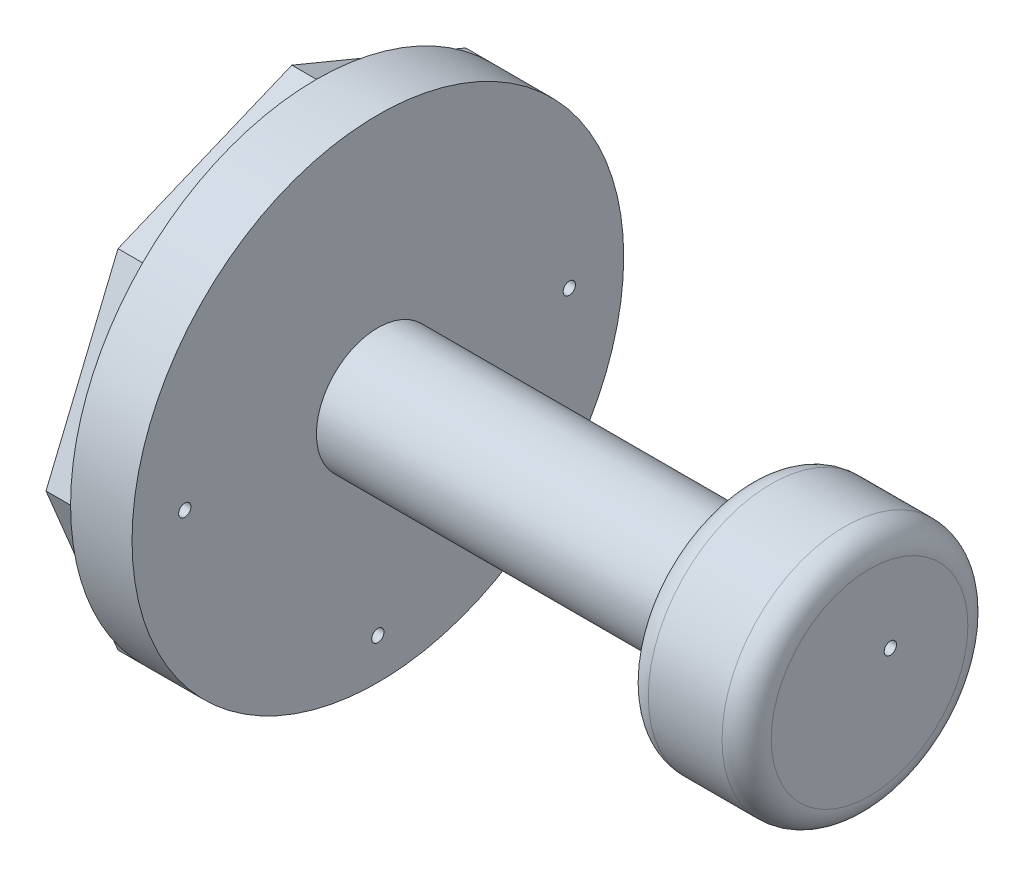
SolidWorks part; units mm, degrees
ref_plane "Front Plane" through (0, 0, 0) normal (0, 0, 1) x (1, 0, 0)
ref_plane "Top Plane" through (0, 0, 0) normal (0, 1, 0) x (1, 0, 0)
ref_plane "Right Plane" through (0, 0, 0) normal (1, 0, 0) x (0, 0, -1)
sketch "Sketch1" plane through (0, 0, 0) normal (0, 0, 1) x (1, 0, 0)
  line L17 (-22.5, 0) -> (22.5, 0)
  line L18 (22.5, 0) -> (22.5, 5)
  line L20 (22.5, 5) -> (22.5, 10)
  line L21 (22.5, 10) -> (12.5, 10)
  line L22 (12.5, 10) -> (12.5, 5)
  line L23 (12.5, 5) -> (-17.5, 5)
  line L24 (-17.5, 5) -> (-17.5, 20)
  line L25 (-17.5, 20) -> (-22.5, 20)
  line L26 (-22.5, 20) -> (-22.5, 0)
  point P0 (0, 0)
  dimension "D5" = 30
  dimension "D6" = 5
  dimension "D7" = 5
  dimension "D1" = 10
  dimension "D2" = 20
  dimension "D3" = 5
  dimension "D4" = 5
revolve "Revolve2" add sketch "Sketch1" angle 360 about L17
fillet "Fillet7" radius 2 1 edges at (22.5, 0, 10)
fillet "Fillet8" radius 2 1 edges at (12.5, 0, 10)
sketch "Sketch2" plane through (-22.5, 0, 0) normal (-1, 0, 0) x (0, 0, 1)
  line L0 (0, 20) -> (-14.1421, 14.1421)
  line L1 (-14.1421, 14.1421) -> (-20, 0)
  line L2 (-20, 0) -> (-14.1421, -14.1421)
  line L3 (-14.1421, -14.1421) -> (0, -20)
  line L4 (0, -20) -> (14.1421, -14.1421)
  line L5 (14.1421, -14.1421) -> (20, 0)
  line L6 (20, 0) -> (14.1421, 14.1421)
  line L7 (14.1421, 14.1421) -> (0, 20)
  line L8 (0, 20) -> (0, -20) construction
  line L9 (-5.3835, 14.7091) -> (-1.3333, 10.3779)
  line L10 (-1.3333, 10.3779) -> (-3.8507, 9.4935)
  line L11 (-11.5701, -4.6843) -> (11.7573, -4.6843)
  line L12 (-7.5, -6.4936) -> (7.5, -6.4936)
  line L13 (-3.8507, 9.4935) -> (-6.4346, 12.2566)
  line L14 (-6.4346, 12.2566) -> (-5.3835, 14.7091)
  line L15 (5.6645, 14.4281) -> (1.3333, 10.3779)
  line L16 (1.3333, 10.3779) -> (3.7858, 9.3269)
  line L17 (3.7858, 9.3269) -> (6.5489, 11.9107)
  line L18 (6.5489, 11.9107) -> (5.6645, 14.4281)
  line L19 (-0.4043, 2.6845) -> (2.5598, -0.8347)
  line L20 (2.5598, -0.8347) -> (-2.1166, -1.1947)
  line L21 (-2.1166, -1.1947) -> (-0.4043, 2.6845)
  circle A0 centre (0, 0) radius 20 construction
  circle A1 centre (0, 0) radius 17.9324
  circle A2 centre (-7.5, 6.8168) radius 1.4702
  circle A3 centre (-7.5, 6.8168) radius 4.0701
  circle A4 centre (7.5, 6.3596) radius 1.4702
  circle A5 centre (7.5, 6.3596) radius 4.0701
  spline S0 degree 2 poles (-11.5701, -4.6843) (0.0193, -23.6004) (11.7573, -4.6843) knots 0 0 0 1 1 1
  spline S1 degree 2 poles (7.5, -6.4936) (0, -19.6713) (-7.5, -6.4936) knots 0 0 0 1 1 1
  dimension "D1" = 7.5
  dimension "D2" = 7.5
  dimension "D3" = 1.3333
  dimension "D4" = 1.3333
extrude "Boss-Extrude4" add sketch "Sketch2" along normal blind 2 contours L8 L0 L1 L2 L3 A1 | L7 L8 A1 L4 L5 L6 | A5 A4 | A3 A2 | L11 L8 L12 S1 S0 | L8 L11 S0 S1 L12 | L14 L9 L10 L13 | L18 L15 L16 L17 | L19 L20 L21
hole_wizard "Ø1.0mm Dowel Hole1" positions "Sketch14" profile "Sketch12" hole size "Ø1.0" standard "ANSI Metric" end condition through all
sketch "Sketch14" plane through (22.5, 0, 0) normal (1, 0, 0) x (0, 0, -1)
  point P0 (1.6937, 1.5774)
sketch "Sketch12" plane through (22.5, 1.5774, -1.6937) normal (0, 1, 0) x (0, 0, -1)
  line L0 (0, 0) -> (0, 47)
  line L1 (0, 47) -> (0.5, 47)
  line L2 (0.5, 47) -> (0.5, 0)
  line L5 (0.5, 0) -> (0, 0)
  line L11 (0, -6.35) -> (0, 107.95) construction
  dimension "Thru Hole Dia." = 1
  dimension "Thru Hole Depth" = 47
hole_wizard "Ø1.0mm Dowel Hole3" positions "Sketch20" profile "Sketch19" hole size "Ø1.0" standard "BSI" end condition through all
sketch "Sketch20" plane through (-22.5, 0, 0) normal (-1, 0, 0) x (0, 0, 1)
  point P0 (15.7081, 0)
  point P2 (-15.5752, 0)
  point P4 (0, -16.6877)
sketch "Sketch19" plane through (-22.5, 0, 15.7081) normal (0, 1, 0) x (0, 0, 1)
  line L0 (0, 0) -> (0, 45)
  line L1 (0, 45) -> (0.5, 45)
  line L2 (0.5, 45) -> (0.5, 0)
  line L5 (0.5, 0) -> (0, 0)
  line L11 (0, -6.35) -> (0, 107.95) construction
  dimension "Thru Hole Dia." = 1
  dimension "Thru Hole Depth" = 45
equation "\"D2@Sketch2\"=\"D1@Sketch2\""
equation "\"D4@Sketch2\"=\"D3@Sketch2\""
equation "\"D4@Sketch1\"=\"D6@Sketch1\""
